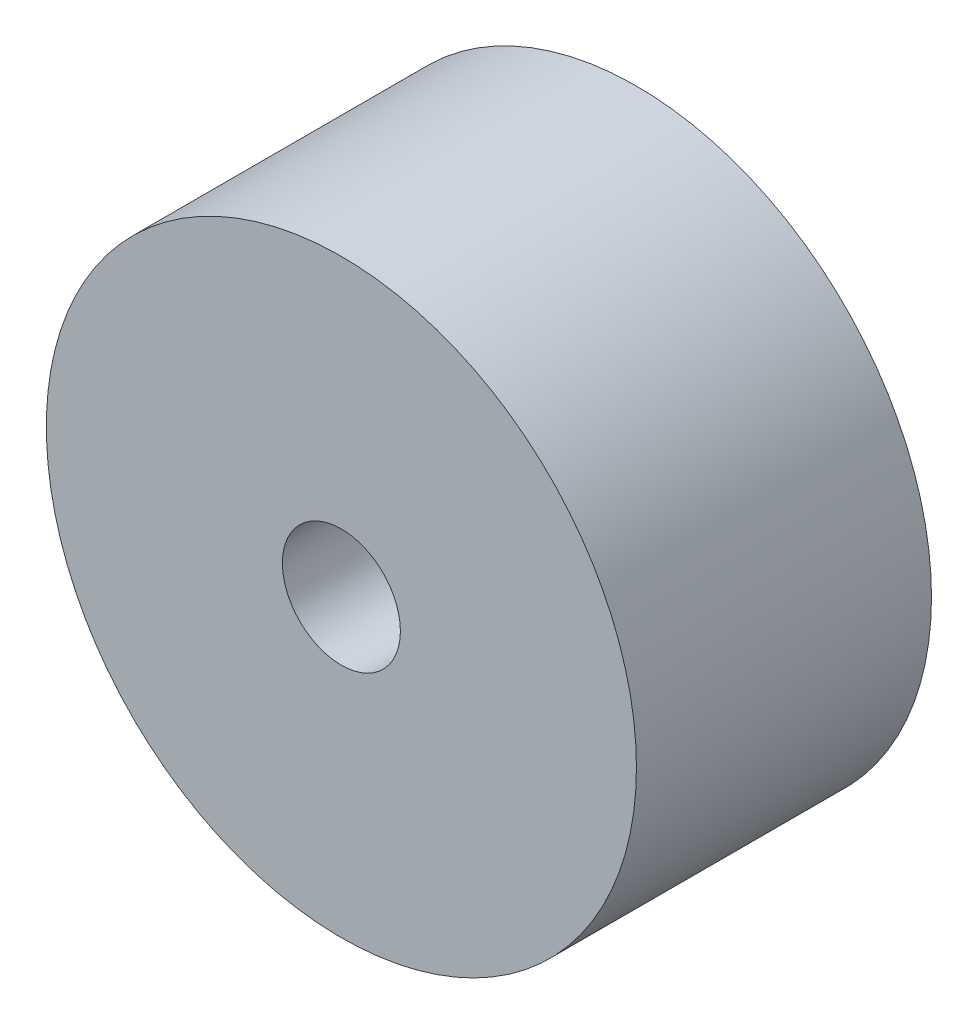
SolidWorks part; units mm, degrees
ref_plane "Alzado" through (0, 0, 0) normal (0, 0, 1) x (1, 0, 0)
ref_plane "Planta" through (0, 0, 0) normal (0, 1, 0) x (1, 0, 0)
ref_plane "Vista lateral" through (0, 0, 0) normal (1, 0, 0) x (0, 0, -1)
sketch "Croquis1" plane through (0, 0, 0) normal (0, 0, 1) x (1, 0, 0)
  circle A0 centre (0, 0) radius 50
  circle A1 centre (0, 0) radius 10
  dimension "D1" = 100
  dimension "D2" = 20
extrude "Saliente-Extruir1" add sketch "Croquis1" along normal blind 50
